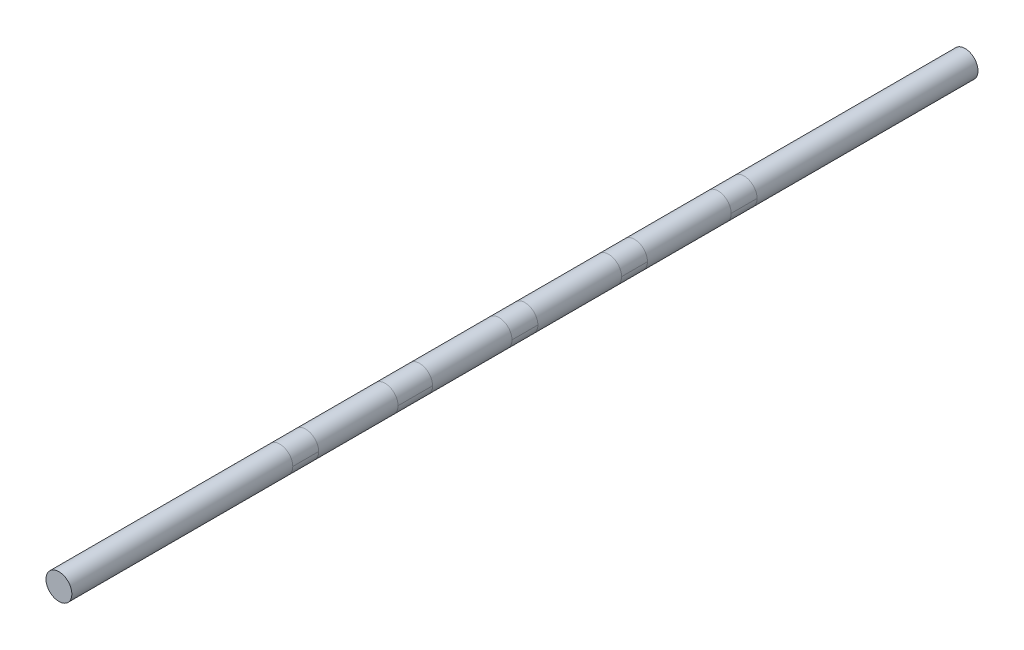
SolidWorks part; units mm, degrees
ref_plane "Front Plane" through (0, 0, 0) normal (0, 0, 1) x (1, 0, 0)
ref_plane "Top Plane" through (0, 0, 0) normal (0, 1, 0) x (1, 0, 0)
ref_plane "Right Plane" through (0, 0, 0) normal (1, 0, 0) x (0, 0, -1)
sketch "Sketch1" plane through (0, 0, 0) normal (0, 0, 1) x (1, 0, 0)
  circle A0 centre (0, 0) radius 14.986
  dimension "D1" = 29.972
extrude "Boss-Extrude1" add sketch "Sketch1" along normal blind 1050
ref_plane "Plane1" through (0, 0, 525) normal (0, 0, 1) x (1, 0, 0)
sketch "Sketch4" plane through (0, 0, 0) normal (0, 1, 0) x (1, 0, 0)
  line L0 (14.986, -1050) -> (14.986, 0) construction
  line L1 (-14.986, -383) -> (14.986, -383)
  line L2 (-14.986, -383) -> (-14.986, -413)
  line L3 (-14.986, -413) -> (14.986, -413)
  line L4 (14.986, -383) -> (14.986, -413)
  line L5 (-14.986, -383) -> (14.986, -413) construction
  line L6 (-14.986, -413) -> (14.986, -383) construction
  line L7 (14.986, 0) -> (-14.986, 0) construction
  line L8 (-14.986, -510) -> (14.986, -510)
  line L9 (-14.986, -510) -> (-14.986, -540)
  line L10 (-14.986, -540) -> (14.986, -540)
  line L11 (14.986, -510) -> (14.986, -540)
  line L12 (-14.986, -510) -> (14.986, -540) construction
  line L13 (-14.986, -540) -> (14.986, -510) construction
  line L14 (-14.986, -764) -> (14.986, -764)
  line L15 (-14.986, -764) -> (-14.986, -794)
  line L16 (-14.986, -794) -> (14.986, -794)
  line L17 (14.986, -764) -> (14.986, -794)
  line L18 (-14.986, -764) -> (14.986, -794) construction
  line L19 (-14.986, -794) -> (14.986, -764) construction
  line L20 (-14.986, -632) -> (14.986, -632)
  line L21 (-14.986, -632) -> (-14.986, -672)
  line L22 (-14.986, -672) -> (14.986, -672)
  line L23 (14.986, -632) -> (14.986, -672)
  line L24 (-14.986, -632) -> (14.986, -672) construction
  line L25 (-14.986, -672) -> (14.986, -632) construction
  line L26 (-14.986, -256) -> (14.986, -256)
  line L27 (-14.986, -256) -> (-14.986, -286)
  line L28 (-14.986, -286) -> (14.986, -286)
  line L29 (14.986, -256) -> (14.986, -286)
  line L30 (-14.986, -256) -> (14.986, -286) construction
  line L31 (-14.986, -286) -> (14.986, -256) construction
  point P0 (0, -398)
  point P7 (0, -525)
  point P12 (0, -779)
  point P17 (0, -652)
  point P22 (0, -271)
  dimension "D1" = 525
  dimension "D2" = 254
  dimension "D3" = 127
  dimension "D4" = 127
  dimension "D5" = 254
  dimension "D6" = 30
  dimension "D7" = 40
  dimension "D8" = 30
  dimension "D9" = 30
  dimension "D10" = 30
split line "Split Line1"
